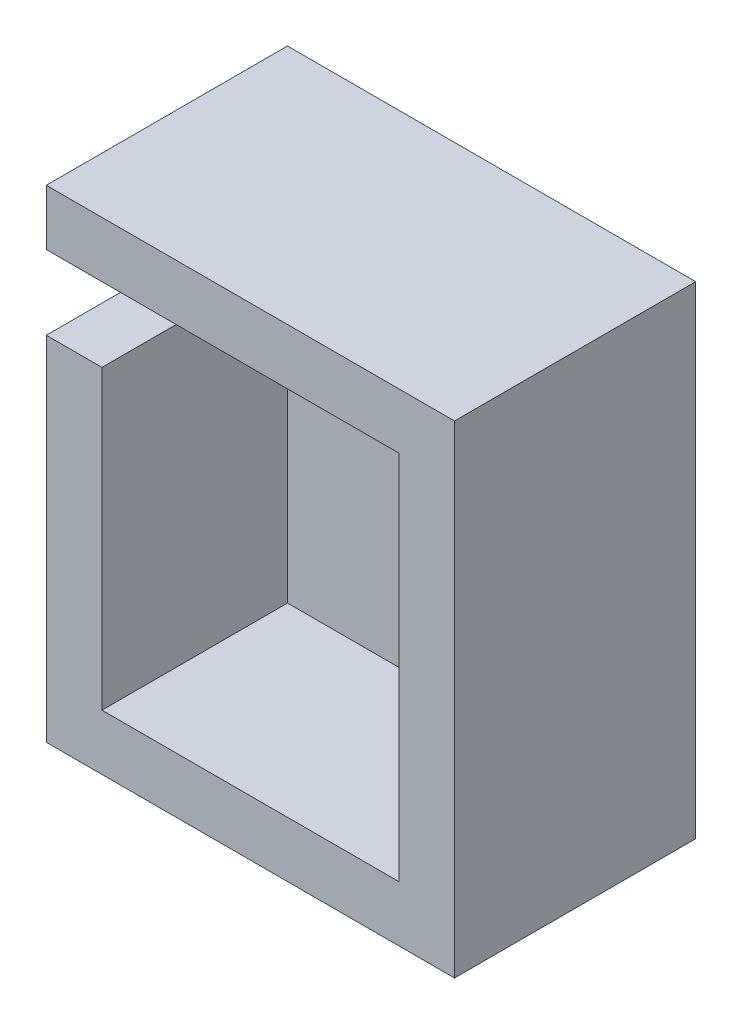
SolidWorks part; units mm, degrees
ref_plane "Front Plane" through (0, 0, 0) normal (0, 0, 1) x (1, 0, 0)
ref_plane "Top Plane" through (0, 0, 0) normal (0, 1, 0) x (1, 0, 0)
ref_plane "Right Plane" through (0, 0, 0) normal (1, 0, 0) x (0, 0, -1)
sketch "Sketch1" plane through (0, 0, 0) normal (0, 0, 1) x (1, 0, 0)
  line L0 (-72.1, 8.9) -> (-53.1, 8.9)
  line L1 (-53.1, 8.9) -> (-53.1, -11.1)
  line L2 (-53.1, -11.1) -> (-69.1, -11.1)
  line L3 (-69.1, -11.1) -> (-69.1, 4.9)
  line L4 (-69.1, 4.9) -> (-72.1, 4.9)
  line L5 (-72.1, 4.9) -> (-72.1, -14.1)
  line L6 (-72.1, -14.1) -> (-50.1, -14.1)
  line L7 (-50.1, -14.1) -> (-50.1, 11.9)
  line L8 (-50.1, 11.9) -> (-72.1, 11.9)
  line L9 (-72.1, 11.9) -> (-72.1, 8.9)
  dimension "D1" = 3
  dimension "D2" = 3
  dimension "D3" = 3
  dimension "D4" = 3
  dimension "D5" = 20
  dimension "D6" = 16
  dimension "D7" = 16
  dimension "D8" = 19
extrude "Boss-Extrude1" add sketch "Sketch1" along normal blind 10
sketch "Sketch2" plane through (0, 0, 0) normal (0, 0, -1) x (-1, 0, 0)
  line L0 (50.1, 11.9) -> (72.1, 11.9)
  line L1 (72.1, 11.9) -> (72.1, -14.1)
  line L2 (72.1, -14.1) -> (50.1, -14.1)
  line L3 (50.1, -14.1) -> (50.1, 11.9)
extrude "Boss-Extrude2" add sketch "Sketch2" along normal blind 3
